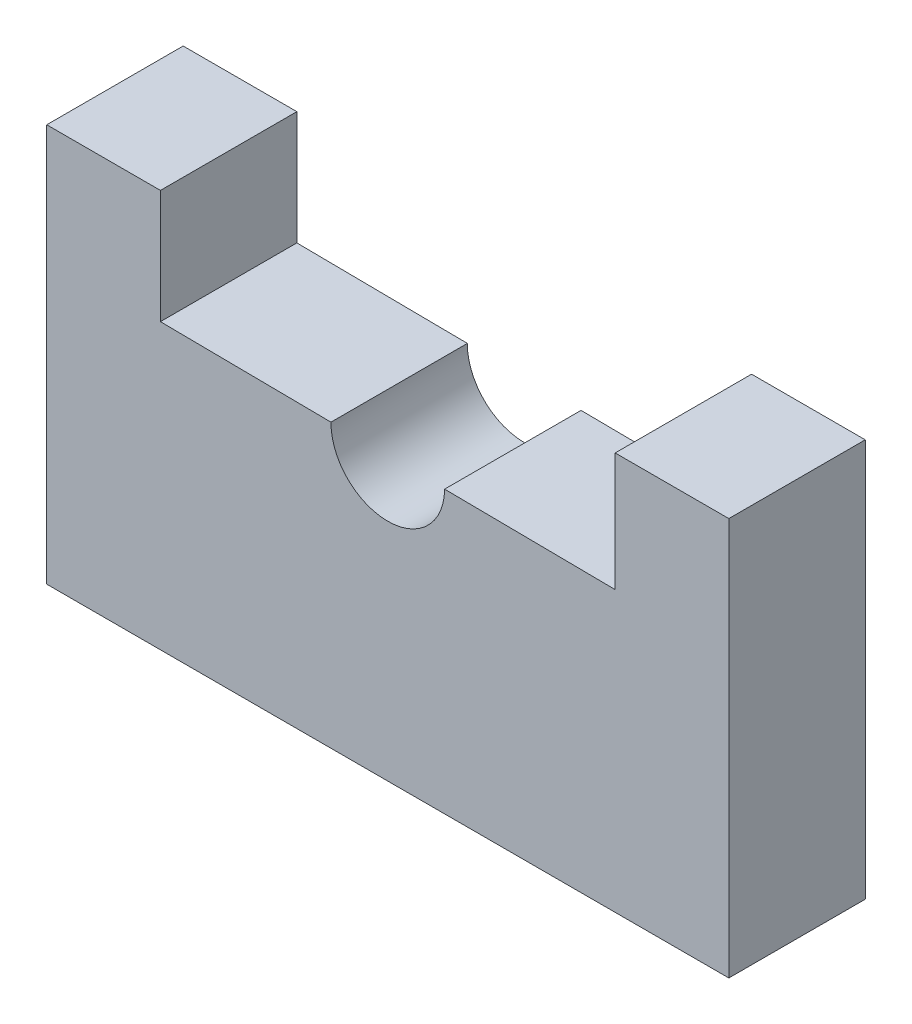
SolidWorks part; units mm, degrees
ref_plane "Front Plane" through (0, 0, 0) normal (0, 0, 1) x (1, 0, 0)
ref_plane "Top Plane" through (0, 0, 0) normal (0, 1, 0) x (1, 0, 0)
ref_plane "Right Plane" through (0, 0, 0) normal (1, 0, 0) x (0, 0, -1)
sketch "Sketch1" plane through (0, 0, 0) normal (0, 0, 1) x (1, 0, 0)
  line L0 (24.1577, 16.9041) -> (34.1577, 16.9041)
  line L1 (-25.8423, 16.9041) -> (-15.8423, 16.9041)
  line L2 (-25.8423, 16.9041) -> (-25.8423, -18.0959)
  line L3 (-25.8423, -18.0959) -> (34.1577, -18.0959)
  line L4 (34.1577, 16.9041) -> (34.1577, -18.0959)
  line L5 (-25.8423, 16.9041) -> (34.1577, -18.0959) construction
  line L6 (-25.8423, -18.0959) -> (34.1577, 16.9041) construction
  line L8 (-15.8423, 16.9041) -> (-15.8423, 6.9041)
  line L10 (24.1577, 16.9041) -> (24.1577, 11.0708)
  line L12 (-15.8423, 6.9041) -> (-0.842, 6.7495)
  line L13 (24.1577, 6.4919) -> (24.1577, 11.0708)
  line L14 (4.1577, 1.698) -> (4.1577, -24.1174) construction
  line L15 (9.1574, 6.6465) -> (24.1577, 6.4919)
  arc A0 (-0.842, 6.7495) -> (9.1574, 6.6465) centre (4.1577, 6.698) ccw
  point P0 (4.1577, -0.5959)
  point P5 (4.1577, 16.9041)
  dimension "D1" = 35
  dimension "D2" = 60
  dimension "D3" = 10
  dimension "D4" = 10
  dimension "D5" = 20
  dimension "D6" = 10
extrude "Boss-Extrude1" add sketch "Sketch1" along normal mid plane 12
